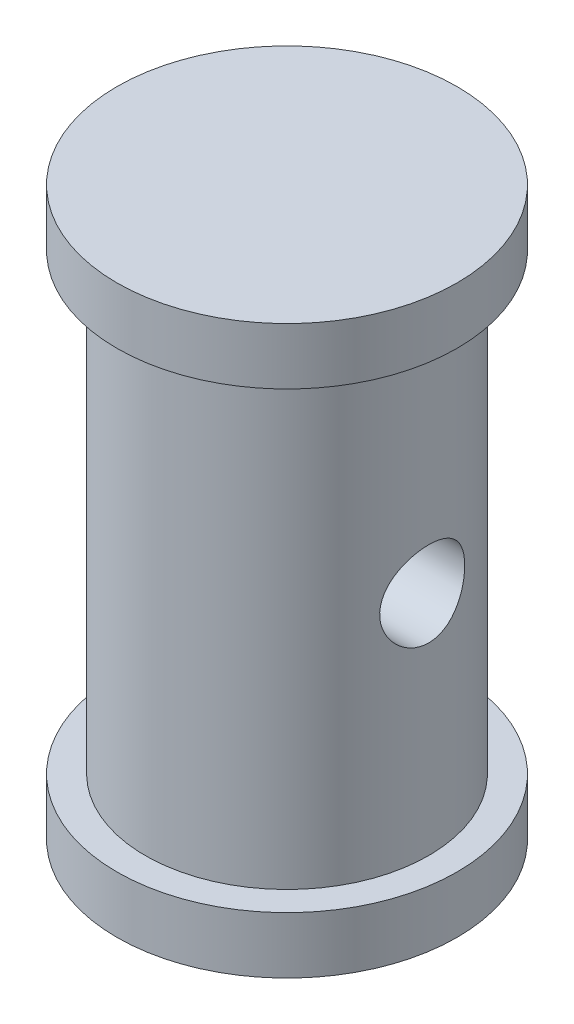
SolidWorks part; units mm, degrees
ref_plane "Alzado" through (0, 0, 0) normal (0, 0, 1) x (1, 0, 0)
ref_plane "Planta" through (0, 0, 0) normal (0, 1, 0) x (1, 0, 0)
ref_plane "Vista lateral" through (0, 0, 0) normal (1, 0, 0) x (0, 0, -1)
sketch "Croquis2" plane through (0, 0, 0) normal (0, 0, 1) x (1, 0, 0)
  line L0 (0, 0) -> (-6, 0)
  line L1 (-6, 0) -> (-6, 2)
  line L2 (-6, 2) -> (-5, 2)
  line L3 (-5, 2) -> (-5, 18)
  line L4 (-5, 18) -> (-6, 18)
  line L5 (-6, 18) -> (-6, 20)
  line L6 (-6, 20) -> (0, 20)
  line L7 (0, 20) -> (0, 0)
  line L8 (0, 0) -> (0, 8.9453) construction
  point P11 (0, 0)
  point P12 (0, 0)
  dimension "D2" = 12
  dimension "D3" = 10
  dimension "D4" = 2
  dimension "D5" = 20
revolve "Revolución1" add sketch "Croquis2" angle 360 about L8
sketch "Croquis3" plane through (0, 0, 0) normal (0, -1, 0) x (1, 0, 0)
  circle A1 centre (0, 0) radius 2.49
  dimension "D1" = 4.98
extrude "Cortar-Extruir1" cut sketch "Croquis3" against normal blind 18
ref_plane "Plano1" through (5, 0, 0) normal (1, 0, 0) x (0, 0, -1)
sketch "Croquis4" plane through (5, 0, 0) normal (1, 0, 0) x (0, 0, -1)
  line L0 (0, 2) -> (0, 18) construction
  line L1 (6, 2) -> (-6, 2) construction
  line L2 (-5, 18) -> (5, 18) construction
  circle A0 centre (0, 10) radius 1.5
  point P8 (2.4228, 9.9557)
  point P9 (0, 10)
  dimension "D1" = 3
extrude "Cortar-Extruir2" cut sketch "Croquis4" against normal blind 3
